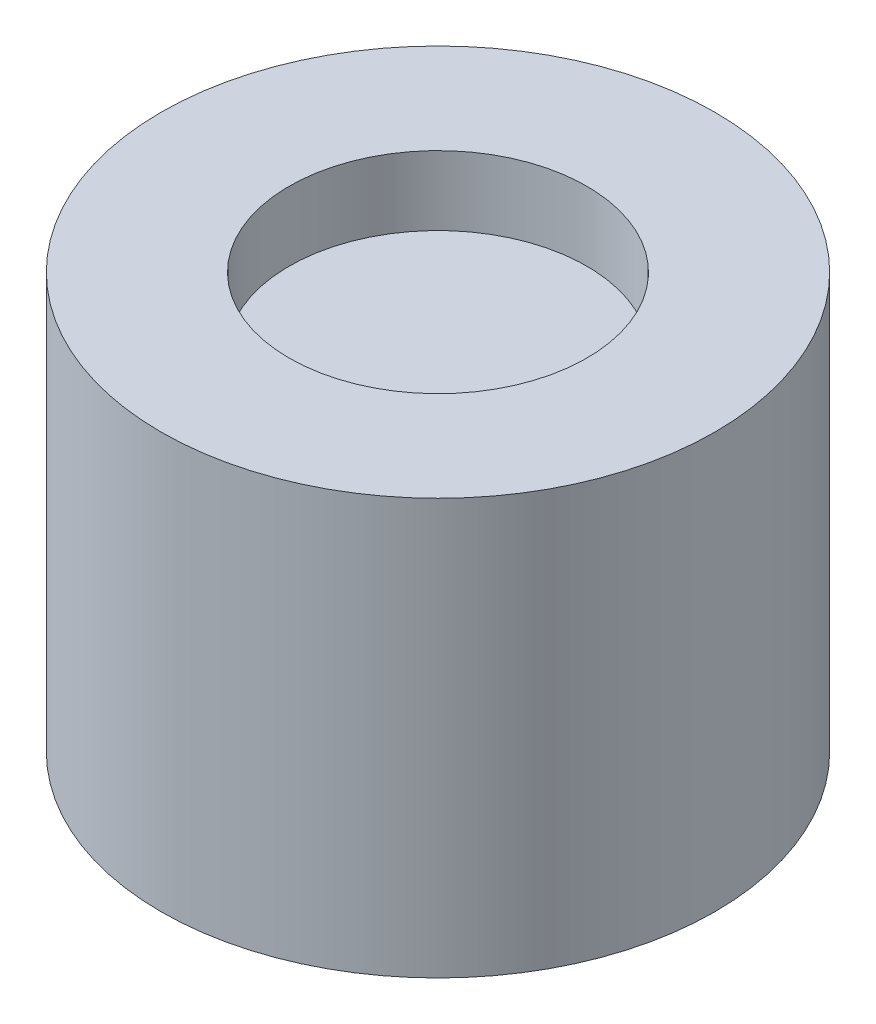
SolidWorks part; units mm, degrees
ref_plane "Front Plane" through (0, 0, 0) normal (0, 0, 1) x (1, 0, 0)
ref_plane "Top Plane" through (0, 0, 0) normal (0, 1, 0) x (1, 0, 0)
ref_plane "Right Plane" through (0, 0, 0) normal (1, 0, 0) x (0, 0, -1)
ref_plane "Plane1"
sketch "Sketch1" plane through (0, 0, 0) normal (0, 1, 0) x (-1, 0, 0)
  circle A0 centre (0, 0) radius 4
  circle A1 centre (0, 0) radius 1.26
  dimension "D1" = 2.52
  dimension "D2" = 8
extrude "Extrusion1" add sketch "Sketch1" along normal blind 4 contours A0 A1
ref_plane "Plane2"
sketch "Sketch2" plane through (0, 4, 0) normal (0, 1, 0) x (1, 0, 0)
  circle A0 centre (0, 0) radius 4
  dimension "D1" = 8
extrude "Extrusion2" add sketch "Sketch2" along normal blind 1
sketch "Sketch3" plane through (0, 5, 0) normal (0, 1, 0) x (-1, 0, 0)
  circle A0 centre (0, 0) radius 4
  circle A1 centre (0, 0) radius 2.15
  circle M1 centre (0, 0) radius 4
  dimension "D1" = 4.3
  dimension "D2" = 8
extrude "Extrusion3" add sketch "Sketch3" along normal blind 1 contours A1 M1
